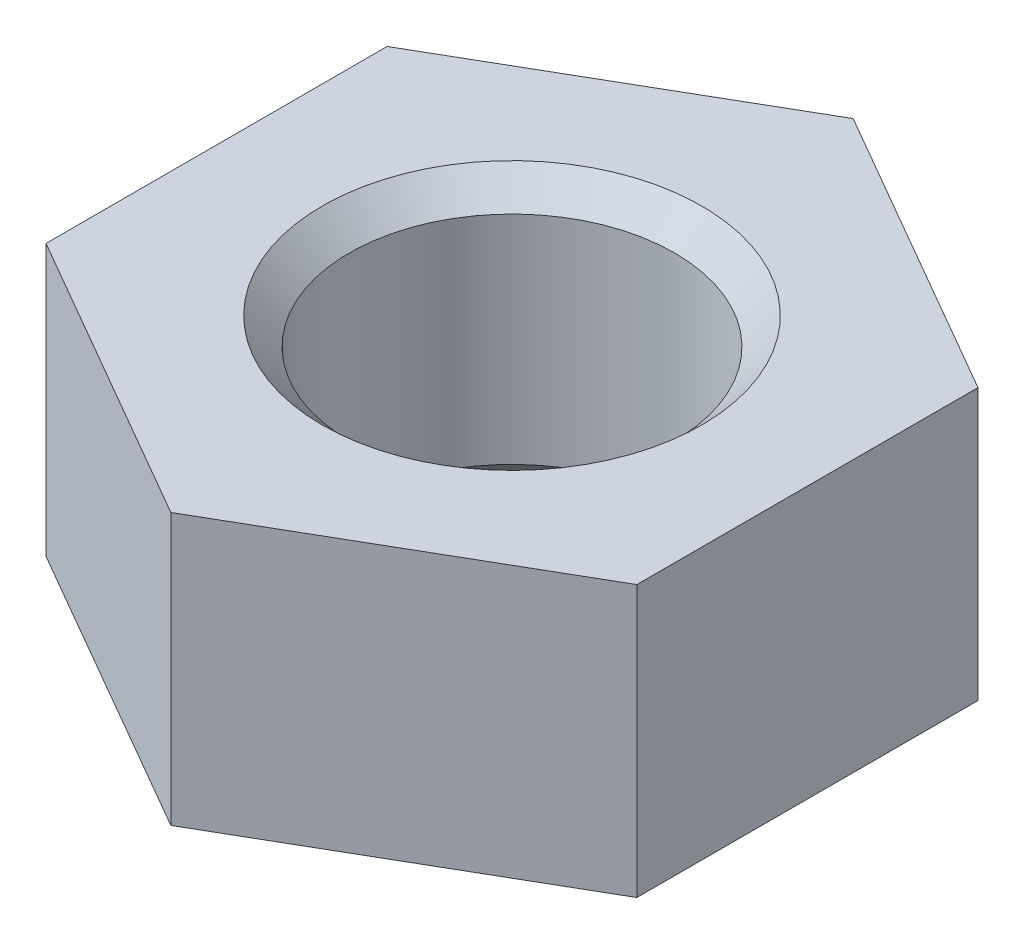
SolidWorks part; units mm, degrees
material "Nylon 101"
ref_plane "Front Plane" through (0, 0, 0) normal (0, 0, 1) x (1, 0, 0)
ref_plane "Top Plane" through (0, 0, 0) normal (0, 1, 0) x (1, 0, 0)
ref_plane "Right Plane" through (0, 0, 0) normal (1, 0, 0) x (0, 0, -1)
sketch "Sketch2" plane through (0, 0, 0) normal (0, 1, 0) x (1, 0, 0)
  line L1 (-2.725, 1.5733) -> (-2.725, -1.5733)
  line L2 (-2.725, -1.5733) -> (0, -3.1466)
  line L3 (0, -3.1466) -> (2.725, -1.5733)
  line L4 (2.725, -1.5733) -> (2.725, 1.5733)
  line L5 (2.725, 1.5733) -> (0, 3.1466)
  line L6 (0, 3.1466) -> (-2.725, 1.5733)
  circle A0 centre (0, 0) radius 2.725 construction
  circle A1 centre (0, 0) radius 1.5
  dimension "D1" = 5.45
  dimension "D2" = 3
extrude "Boss-Extrude1" add sketch "Sketch2" along normal mid plane 2.5
chamfer "Chamfer1" distance 0.25 angle 45 2 edges at (0, -1.25, 1.5) (0, 1.25, 1.5)
